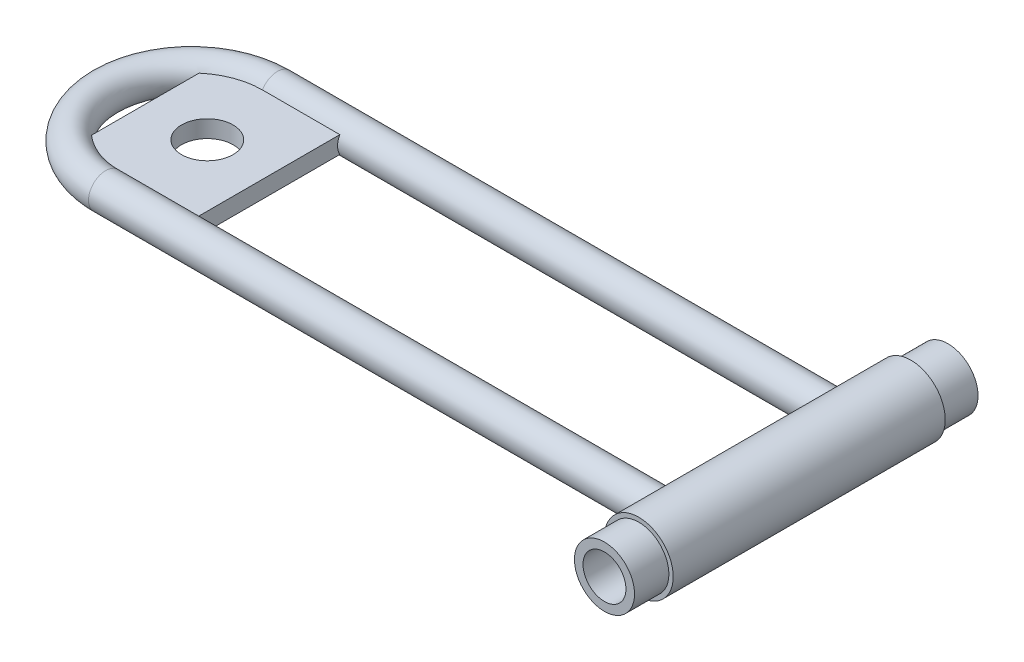
SolidWorks part; units mm, degrees
ref_plane "Front Plane" through (0, 0, 0) normal (0, 0, 1) x (1, 0, 0)
ref_plane "Top Plane" through (0, 0, 0) normal (0, 1, 0) x (1, 0, 0)
ref_plane "Right Plane" through (0, 0, 0) normal (1, 0, 0) x (0, 0, -1)
sketch "Sketch1" plane through (0, 0, 0) normal (0, 0, 1) x (1, 0, 0)
  circle A0 centre (0, 0) radius 6.35
  circle A1 centre (0, 0) radius 3.175
  dimension "D1" = 12.7
  dimension "D2" = 3.175
extrude "Boss-Extrude1" add sketch "Sketch1" along normal blind 62.992
ref_plane "Plane1" through (-3.81, 0, 0) normal (-1, 0, 0) x (0, 0, 1)
sketch "Sketch3" plane through (-3.81, 0, 0) normal (-1, 0, 0) x (0, 0, 1)
  line L0 (0, 0) -> (62.992, 0)
  line L1 (62.992, -6.35) -> (62.992, 6.35) construction
  circle A0 centre (-15.748, 0) radius 3.175
  circle A1 centre (47.244, 0) radius 3.175
  dimension "D3" = 6.35
  dimension "D4" = 6.35
  dimension "D1" = 15.748
  dimension "D2" = 15.748
sketch "Sketch4" plane through (0, 0, 0) normal (0, 1, 0) x (1, 0, 0)
  line L0 (-3.81, -15.6639) -> (-107.95, -15.6639)
  line L1 (-3.81, 0) -> (-3.81, -62.992) construction
  line L2 (-3.81, -47.0944) -> (-107.95, -47.0944)
  line L3 (-6.35, 0) -> (-6.35, -62.992) construction
  arc A0 (-107.95, -15.6639) -> (-107.95, -47.0944) centre (-107.95, -31.3792) ccw
  dimension "D1" = 101.6
sweep "Sweep1" add profiles "Sketch3" path "Sketch4"
ref_plane "Plane2" through (0, 0, 15.24) normal (0, 0, 1) x (1, 0, 0)
sketch "Sketch6" plane through (0, 0, 15.24) normal (0, 0, 1) x (1, 0, 0)
  line L0 (-116.5013, 0) -> (-93.6413, 0)
  line L3 (-93.6413, 0) -> (-116.5013, 0)
  line L4 (-93.6413, 0) -> (-93.6413, -1.5875)
  line L5 (-93.6413, -1.5875) -> (-116.5013, -1.5875)
  line L6 (-116.5013, 0) -> (-116.5013, -1.5875)
  line L7 (-93.6413, 0) -> (-116.5013, 0)
  line L8 (-93.6413, 0) -> (-93.6413, 1.5875)
  line L9 (-93.6413, 1.5875) -> (-116.5013, 1.5875)
  line L10 (-116.5013, 0) -> (-116.5013, 1.5875)
  point P3 (-105.0713, 0)
  dimension "D1" = 22.86
  dimension "D2" = 1.5875
  dimension "D3" = 1.5875
extrude "Boss-Extrude3" add sketch "Sketch6" along normal blind 29.21 contours L0 L6 L5 L4 | L10 L0 L8 L9
sketch "Sketch7" plane through (0, 1.5875, 0) normal (0, 1, 0) x (1, 0, 0)
  line L1 (-93.6413, -44.45) -> (-93.6413, -18.2639) construction
  circle A0 centre (-105.0713, -31.3411) radius 4.7625
  dimension "D3" = 9.525
  dimension "D1" = 11.43
  dimension "D2" = 9.906
extrude "Cut-Extrude1" cut sketch "Sketch7" against normal blind 29.21
sketch "Sketch9" plane through (0, 0, 0) normal (0, 0, -1) x (-1, 0, 0)
  circle A0 centre (0, 0) radius 6.35
  circle A1 centre (0, 0) radius 3.175
ref_plane "Plane3" through (0, 0, 31.496) normal (0, 0, 1) x (1, 0, 0)
extrude "Boss-Extrude5" add sketch "Sketch9" along normal blind 6.35
mirror "Mirror1" about plane through (0, 0, 31.496) normal (0, 0, 1) of "Boss-Extrude5"
sketch "Sketch10" plane through (0, 0, 69.342) normal (0, 0, 1) x (1, 0, 0)
  circle A0 centre (0, 0) radius 5.5562
  circle A1 centre (0, 0) radius 6.35
  dimension "D1" = 11.1125
  dimension "D2" = 12.7
extrude "Cut-Extrude6" cut sketch "Sketch10" against normal blind 12.7
sketch "Sketch12" plane through (0, 0, -6.35) normal (0, 0, -1) x (-1, 0, 0)
  circle A0 centre (0, 0) radius 5.5562
  circle A1 centre (0, 0) radius 6.35
  dimension "D1" = 11.1125
extrude "Cut-Extrude7" cut sketch "Sketch12" against normal blind 12.7
sketch "Sketch13" plane through (0, 0, 69.342) normal (0, 0, 1) x (1, 0, 0)
  circle A0 centre (0, 0) radius 5.5563
  circle A1 centre (0, 0) radius 3.175
  circle A2 centre (0, 0) radius 3.175 construction
  dimension "D1" = 6.35
  dimension "D2" = 11.1125
extrude "Cut-Extrude8" cut sketch "Sketch13" against normal blind 6.35
sketch "Sketch14" plane through (0, 0, -6.35) normal (0, 0, -1) x (-1, 0, 0)
  circle A0 centre (0, 0) radius 5.5563
  circle A1 centre (0, 0) radius 3.175
  circle A2 centre (0, 0) radius 3.175 construction
  dimension "D1" = 6.35
  dimension "D2" = 11.1125
extrude "Cut-Extrude9" cut sketch "Sketch14" against normal blind 6.35
sketch "Sketch16" plane through (0, 0, 0) normal (0, 0, -1) x (-1, 0, 0)
  circle A0 centre (0, 0) radius 3.9688
  dimension "D1" = 7.9375
extrude "Cut-Extrude11" cut sketch "Sketch16" against normal through all
sketch "Sketch18" plane through (0, 0, 0) normal (0, 0, -1) x (-1, 0, 0)
  circle A0 centre (0, 0) radius 5.5563
  circle A1 centre (0, 0) radius 3.9688
  circle A2 centre (0, 0) radius 3.9688 construction
  dimension "D1" = 7.9375
  dimension "D2" = 11.1125
extrude "Boss-Extrude7" add sketch "Sketch18" along normal blind 0.508
